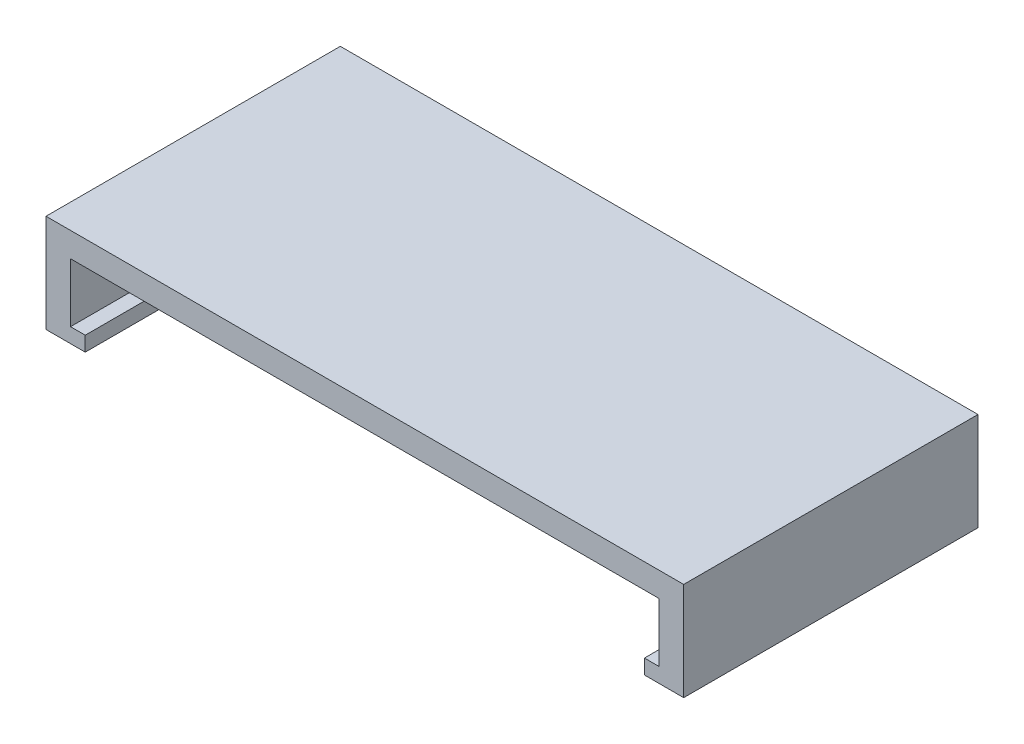
SolidWorks part; units mm, degrees
ref_plane "정면" through (0, 0, 0) normal (0, 0, 1) x (1, 0, 0)
ref_plane "윗면" through (0, 0, 0) normal (0, 1, 0) x (1, 0, 0)
ref_plane "우측면" through (0, 0, 0) normal (1, 0, 0) x (0, 0, -1)
sketch "스케치1" plane through (0, 0, 0) normal (0, 0, 1) x (1, 0, 0)
  line L0 (28.0632, 7.5) -> (37.2807, 7.5)
  line L2 (0, 0) -> (0, 10)
  line L3 (0, 10) -> (65, 10)
  line L4 (65, 0) -> (65, 10)
  line L6 (2.5, 1.5) -> (2.5, 7.5)
  line L7 (2.5, 7.5) -> (62.5, 7.5)
  line L8 (62.5, 1.5) -> (62.5, 7.5)
  line L13 (0, 0) -> (0, 1.5)
  line L14 (0, 0) -> (4, 0)
  line L15 (2.5, 1.5) -> (4, 1.5)
  line L16 (4, 0) -> (4, 1.5)
  line L17 (65, 0) -> (65, 1.5)
  line L18 (65, 0) -> (61, 0)
  line L19 (62.5, 1.5) -> (61, 1.5)
  line L20 (61, 0) -> (61, 1.5)
  dimension "D1" = 65
  dimension "D2" = 2.5
  dimension "D3" = 2.5
  dimension "D4" = 10
  dimension "D6" = 1.5
  dimension "D7" = 1.5
  dimension "D8" = 4
  dimension "D9" = 4
extrude "보스-돌출1" add sketch "스케치1" along normal blind 30 contours L20 L18 L4 L3 L2 L14 L16 L15 L6 L7 L0 L8 L19
